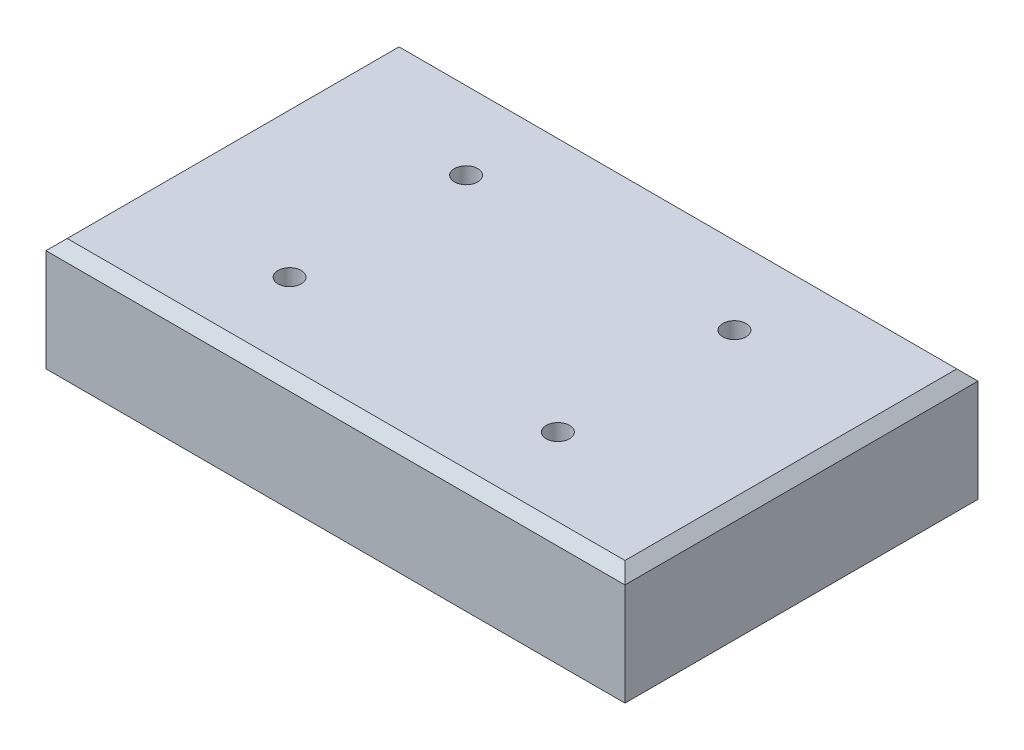
SolidWorks part; units mm, degrees
ref_plane "Front Plane" through (0, 0, 0) normal (0, 0, 1) x (1, 0, 0)
ref_plane "Top Plane" through (0, 0, 0) normal (0, 1, 0) x (1, 0, 0)
ref_plane "Right Plane" through (0, 0, 0) normal (1, 0, 0) x (0, 0, -1)
sketch "Sketch1" plane through (0, 0, 0) normal (0, 1, 0) x (1, 0, 0)
  line L1 (41, -25) -> (-41, -25)
  line L2 (41, -25) -> (41, 25)
  line L3 (41, 25) -> (-41, 25)
  line L4 (-41, -25) -> (-41, 25)
  line L5 (41, -25) -> (-41, 25) construction
  line L6 (41, 25) -> (-41, -25) construction
  point P0 (0, 0)
  dimension "D1" = 50
  dimension "D2" = 82
extrude "Boss-Extrude2" add sketch "Sketch1" along normal blind 16
chamfer "Chamfer1" distance 1.5 angle 45 4 edges at (0, 16, -25) (41, 16, 0) (0, 16, 25) (-41, 16, 0)
ref_plane "Plane1" through (0, 16, 0) normal (0, 1, 0) x (1, 0, 0)
sketch "Sketch2" plane through (0, 16, 0) normal (0, 1, 0) x (1, 0, 0)
  line L0 (0, 0) -> (0, 31.2381) construction
  line L1 (-36.8994, 0) -> (28.0031, 0) construction
  circle A0 centre (-19, 12.5) radius 2
  circle A1 centre (19, 12.5) radius 2
  circle A2 centre (19, -12.5) radius 2
  circle A3 centre (-19, -12.5) radius 2
  dimension "D1" = 19
  dimension "D2" = 12.5
hole_wizard "M4 Tapped Hole1" positions "Sketch3" profile "Sketch4" tap size "M4" standard "DIN"
sketch "Sketch3" plane through (0, 16, 0) normal (0, 1, 0) x (1, 0, 0)
  point P0 (-19, 12.5)
  point P3 (19, 12.5)
  point P6 (19, -12.5)
  point P9 (-19, -12.5)
sketch "Sketch4" plane through (-19, 16, -12.5) normal (1, 0, 0) x (0, 0, 1)
  line L0 (0, 0) -> (0, 8.9914)
  line L1 (0, 8.9914) -> (1.65, 8)
  line L2 (1.65, 8) -> (1.65, 0)
  line L5 (1.65, 0) -> (0, 0)
  line L10 (0, 8.9914) -> (-1.65, 8) construction
  line L11 (0, -6.35) -> (0, 107.95) construction
  dimension "Tap Drill Dia." = 3.3
  dimension "Tap Drill Depth" = 8
  dimension "Drill Angle" = 118
cosmetic thread "Hole Thread1" parameters "D1"=6, "D2"=4
cosmetic thread "Hole Thread2" parameters "D1"=6, "D2"=4
cosmetic thread "Hole Thread3" parameters "D1"=6, "D2"=4
cosmetic thread "Hole Thread4" parameters "D1"=6, "D2"=4
